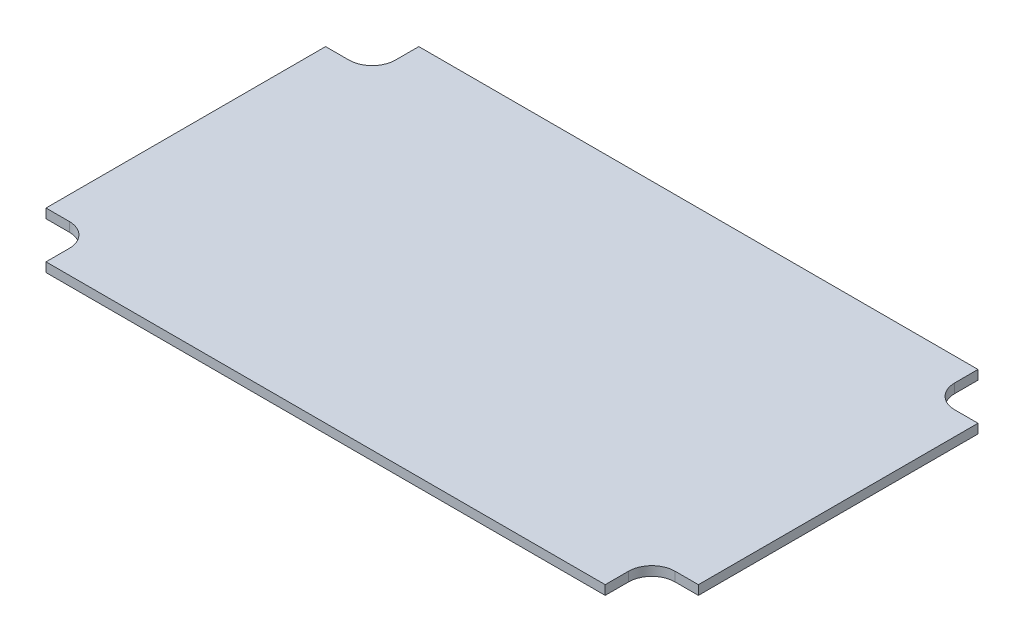
SolidWorks part; units mm, degrees
ref_plane "Front Plane" through (0, 0, 0) normal (0, 0, 1) x (1, 0, 0)
ref_plane "Top Plane" through (0, 0, 0) normal (0, 1, 0) x (1, 0, 0)
ref_plane "Right Plane" through (0, 0, 0) normal (1, 0, 0) x (0, 0, -1)
sketch "Sketch1" plane through (0, 0, 0) normal (0, 1, 0) x (1, 0, 0)
  line L0 (70, 30) -> (60, 30)
  line L1 (-70, 40) -> (70, 40)
  line L2 (-70, 40) -> (-70, -40)
  line L3 (-70, -40) -> (70, -40)
  line L4 (70, 40) -> (70, -40)
  line L5 (-70, 40) -> (70, -40) construction
  line L6 (-70, -40) -> (70, 40) construction
  line L7 (60, 30) -> (60, 40)
  line L8 (0, 0) -> (26.6657, 0) construction
  line L9 (0, 0) -> (0, 20) construction
  line L10 (58, 40) -> (58, 28)
  line L11 (58, 28) -> (70, 28)
  line L12 (-60, 40) -> (-70, 30) construction
  line L13 (-60, 30) -> (-70, 40) construction
  line L14 (-58, 28) -> (-70, 28)
  line L15 (-58, 40) -> (-58, 28)
  line L16 (60, 30) -> (70, 40) construction
  line L17 (60, 40) -> (70, 30) construction
  line L18 (-60, 30) -> (-60, 40)
  line L19 (-70, 30) -> (-60, 30)
  line L20 (60, -40) -> (70, -30) construction
  line L21 (60, -30) -> (70, -40) construction
  line L22 (-60, -30) -> (-70, -40) construction
  line L23 (-60, -40) -> (-70, -30) construction
  line L24 (-70, -30) -> (-60, -30)
  line L25 (-60, -30) -> (-60, -40)
  line L26 (-58, -40) -> (-58, -28)
  line L27 (-58, -28) -> (-70, -28)
  line L28 (58, -28) -> (70, -28)
  line L29 (58, -40) -> (58, -28)
  line L30 (60, -30) -> (60, -40)
  line L31 (70, -30) -> (60, -30)
  line L32 (-68, 28) -> (-68, -28)
  line L33 (-58, -38) -> (58, -38)
  line L34 (68, 28) -> (68, -28)
  line L35 (58, 38) -> (-58, 38)
  circle A0 centre (65, 35) radius 2.25
  circle A1 centre (-65, 35) radius 2.25
  circle A2 centre (-65, -35) radius 2.25
  circle A3 centre (65, -35) radius 2.25
  point P0 (0, 0)
  dimension "D4" = 4.5
  dimension "D1" = 80
  dimension "D2" = 140
  dimension "D3" = 10
  dimension "D5" = 2
  dimension "D6" = 2
  dimension "D7" = 2
  dimension "D8" = 2
  dimension "D9" = 2
extrude "Boss-Extrude8" add sketch "Sketch1" along normal blind 2 contours L32 L14 L2 L27 | L19 L2 L14 L15 L1 L18 | L35 L10 L1 L15 | L10 L35 L15 L14 L32 L27 L26 L33 L29 L28 L34 L11 | L10 L11 L4 L0 L7 L1 | L11 L34 L28 L4 | L31 L4 L28 L29 L3 L30 | L33 L26 L3 L29 | L26 L27 L2 L24 L25 L3
fillet "Fillet1" radius 5 4 edges at (60, 1, 30) (60, 1, -30) (-60, 1, -30) (-60, 1, 30)
